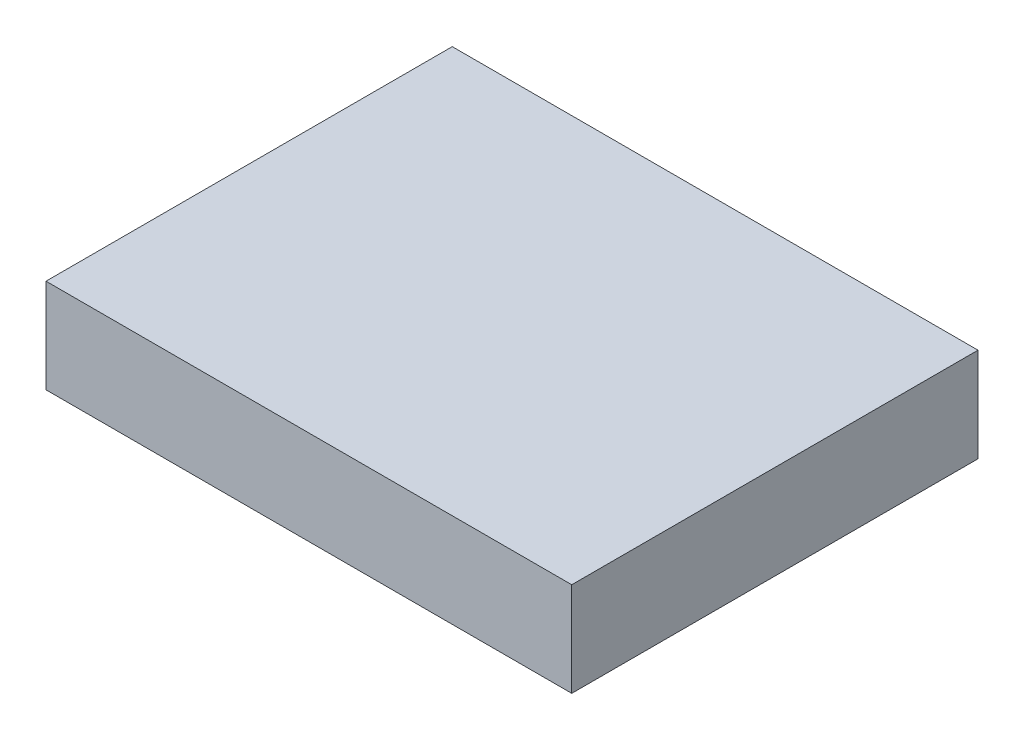
SolidWorks part; units mm, degrees
ref_plane "Front Plane" through (0, 0, 0) normal (0, 0, 1) x (1, 0, 0)
ref_plane "Top Plane" through (0, 0, 0) normal (0, 1, 0) x (1, 0, 0)
ref_plane "Right Plane" through (0, 0, 0) normal (1, 0, 0) x (0, 0, -1)
sketch "Sketch1" plane through (0, 0, 0) normal (0, 1, 0) x (1, 0, 0)
  line L1 (-139.7, -107.95) -> (139.7, -107.95)
  line L2 (-139.7, -107.95) -> (-139.7, 107.95)
  line L3 (-139.7, 107.95) -> (139.7, 107.95)
  line L4 (139.7, -107.95) -> (139.7, 107.95)
  line L5 (-139.7, -107.95) -> (139.7, 107.95) construction
  line L6 (-139.7, 107.95) -> (139.7, -107.95) construction
  point P0 (0, 0)
  dimension "D1" = 215.9
  dimension "D2" = 279.4
extrude "Boss-Extrude1" add sketch "Sketch1" along normal blind 50
